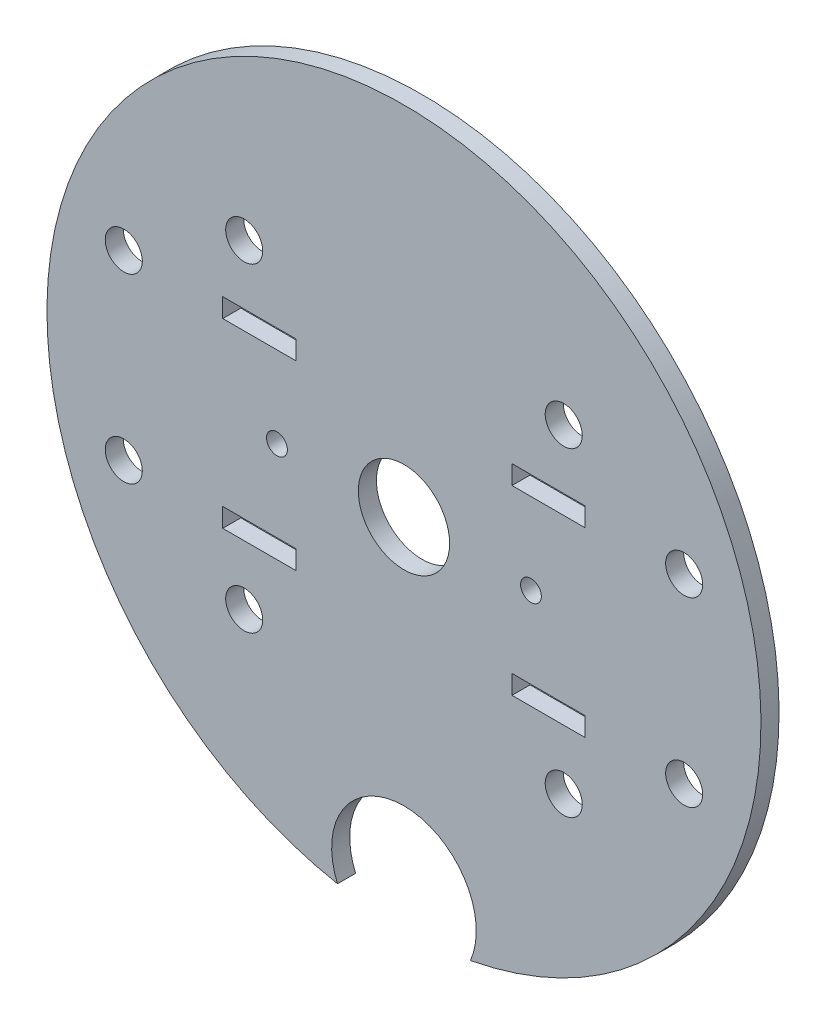
SolidWorks part; units mm, degrees
ref_plane "前视基准面" through (0, 0, 0) normal (0, 0, 1) x (1, 0, 0)
ref_plane "上视基准面" through (0, 0, 0) normal (0, 1, 0) x (1, 0, 0)
ref_plane "右视基准面" through (0, 0, 0) normal (1, 0, 0) x (0, 0, -1)
sketch "草图1" plane through (0, 0, 0) normal (0, 0, 1) x (1, 0, 0)
  line L0 (0, 0) -> (0, -39.5) construction
  line L1 (0, 0) -> (-16.3098, -16.3098) construction
  line L2 (0, 0) -> (16, 0) construction
  line L3 (16, 0) -> (16, 10.05) construction
  line L4 (20.05, -11.1) -> (20.05, -9)
  line L5 (11.95, 11.1) -> (20.05, 11.1)
  line L6 (11.95, 11.1) -> (11.95, 9)
  line L7 (11.95, 9) -> (20.05, 9)
  line L8 (20.05, 11.1) -> (20.05, 9)
  line L9 (11.95, 11.1) -> (20.05, 9) construction
  line L10 (11.95, 9) -> (20.05, 11.1) construction
  line L11 (11.95, -9) -> (20.05, -9)
  line L12 (11.95, -11.1) -> (11.95, -9)
  line L13 (11.95, -11.1) -> (20.05, -11.1)
  line L14 (-20.05, 11.1) -> (-20.05, 9)
  line L15 (-11.95, 11.1) -> (-11.95, 9)
  line L16 (-11.95, 11.1) -> (-20.05, 11.1)
  line L17 (-11.95, 9) -> (-20.05, 9)
  line L18 (-11.95, -11.1) -> (-11.95, -9)
  line L19 (-11.95, -9) -> (-20.05, -9)
  line L20 (-20.05, -11.1) -> (-20.05, -9)
  line L21 (-11.95, -11.1) -> (-20.05, -11.1)
  line L22 (16, 10.05) -> (31, 10.05) construction
  line L23 (0, 0) -> (-14.05, 0) construction
  circle A0 centre (0, 0) radius 5.05
  circle A1 centre (0, 0) radius 39.5 construction
  circle A2 centre (0, 0) radius 25 construction
  circle A3 centre (-17.6777, -17.6777) radius 2.05
  circle A4 centre (-17.6777, 17.6777) radius 2.05
  circle A5 centre (17.6777, 17.6777) radius 2.05
  circle A6 centre (17.6777, -17.6777) radius 2.05
  arc A9 (-7.355, -38.8092) -> (7.355, -38.8092) centre (0, 0) cw
  circle A10 centre (0, 0) radius 12 construction
  arc A11 (-7.355, -38.8092) -> (7.355, -38.8092) centre (0, -35.6621) cw
  circle A12 centre (31, 10.05) radius 2.05
  circle A13 centre (31, -10.05) radius 2.05
  circle A14 centre (-31, -10.05) radius 2.05
  circle A15 centre (-31, 10.05) radius 2.05
  circle A20 centre (-14.05, 0) radius 2.05 construction
  circle A21 centre (14.05, 0) radius 2.05 construction
  circle A22 centre (-14.05, 0) radius 1.15
  circle A23 centre (14.05, 0) radius 1.15
  dimension "D1" = 10.1
  dimension "D2" = 79
  dimension "D4" = 50
  dimension "D5" = 4
  dimension "D6" = 24
  dimension "D11" = 4.1
  dimension "D12" = 18
  dimension "D13" = 4.1
  dimension "D3" = 45
  dimension "D7" = 8.1
  dimension "D8" = 16
  dimension "D9" = 2.1
  dimension "D10" = 15
extrude "凸台-拉伸1" add sketch "草图1" along normal blind 2
